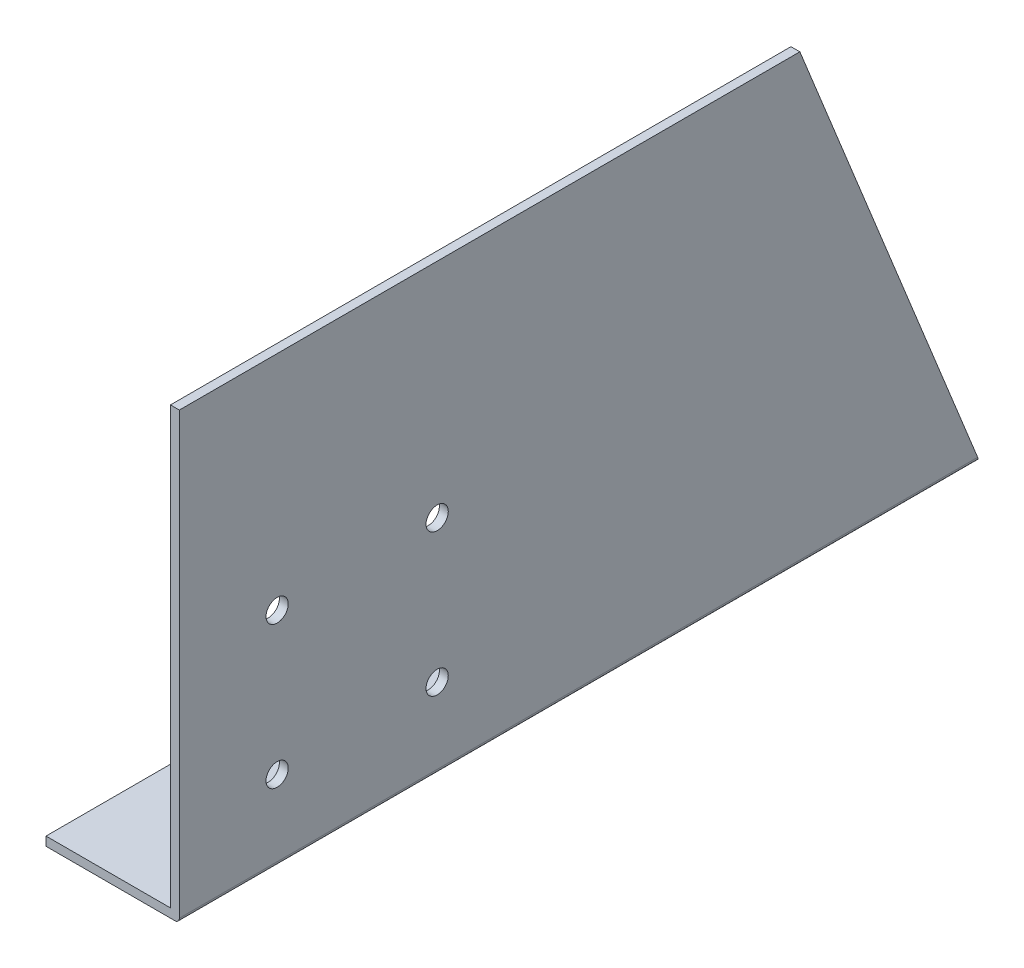
SolidWorks part; units mm, degrees
ref_plane "Front Plane" through (0, 0, 0) normal (0, 0, 1) x (1, 0, 0)
ref_plane "Top Plane" through (0, 0, 0) normal (0, 1, 0) x (1, 0, 0)
ref_plane "Right Plane" through (0, 0, 0) normal (1, 0, 0) x (0, 0, -1)
sketch "Sketch1" plane through (0, 0, 0) normal (0, 0, 1) x (1, 0, 0)
  line L0 (0, 0) -> (30, 0)
  line L1 (30, 0) -> (30, 100)
  line L2 (30, 100) -> (28, 100)
  line L3 (28, 100) -> (28, 2)
  line L4 (28, 2) -> (0, 2)
  line L5 (0, 2) -> (0, 0)
  dimension "D1" = 2
  dimension "D2" = 30
  dimension "D3" = 2
  dimension "D4" = 100
extrude "Boss-Extrude1" add sketch "Sketch1" along normal blind 180
sketch "Sketch2" plane through (30, 0, 0) normal (1, 0, 0) x (0, 0, -1)
  line L0 (0, 0) -> (0, 100)
  line L1 (0, 100) -> (-40.4026, 100)
  line L2 (-180, 100) -> (0, 100) construction
  line L3 (-40.4026, 100) -> (0, 0)
  line L4 (-180, 0) -> (-180, 100) construction
  line L5 (-180, 0) -> (0, 0) construction
  line L6 (-140, 55.5614) -> (-140, 18) construction
  circle A0 centre (-122, 50) radius 2.5
  circle A1 centre (-122, 18) radius 2.5
  circle A2 centre (-158, 18) radius 2.5
  circle A3 centre (-158, 50) radius 2.5
  dimension "D2" = 58
  dimension "D4" = 58
  dimension "D1" = 22
  dimension "D3" = 50
  dimension "D5" = 32
  dimension "D6" = 18
extrude "Cut-Extrude1" cut sketch "Sketch2" against normal blind 180
fillet "Fillet1" radius 1 1 edges at (30, 0, 90)
